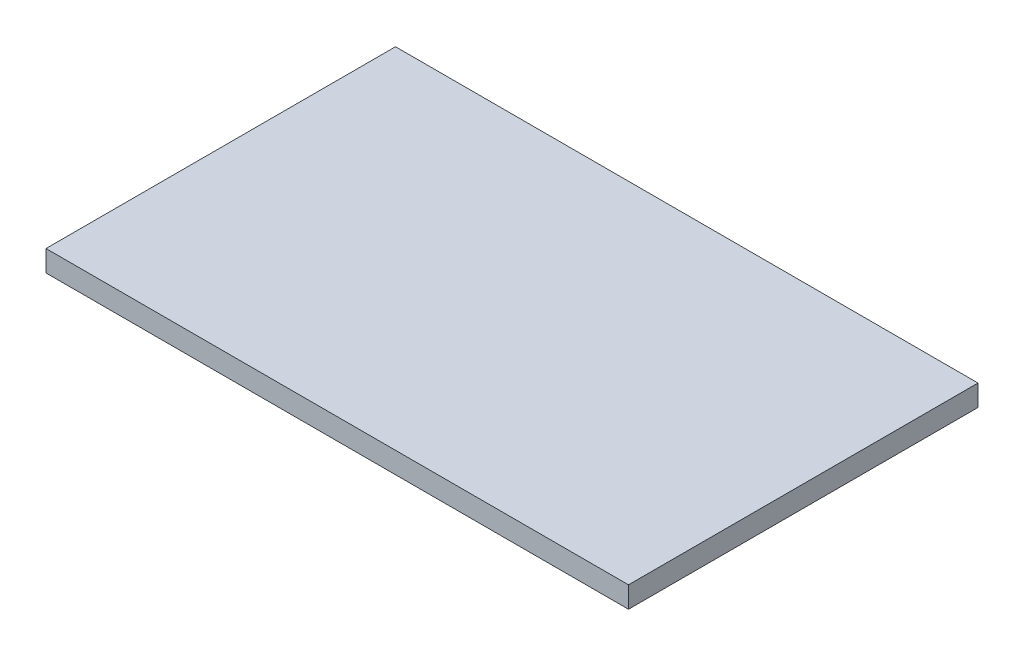
SolidWorks part; units mm, degrees
material "ABS"
ref_plane "Спереди" through (0, 0, 0) normal (0, 0, 1) x (1, 0, 0)
ref_plane "Сверху" through (0, 0, 0) normal (0, 1, 0) x (1, 0, 0)
ref_plane "Справа" through (0, 0, 0) normal (1, 0, 0) x (0, 0, -1)
sketch "Эскиз1" plane through (0, 0, 0) normal (0, 1, 0) x (1, 0, 0)
  line L1 (0, 0) -> (550, 0)
  line L2 (0, 0) -> (0, 330)
  line L3 (0, 330) -> (550, 330)
  line L4 (550, 0) -> (550, 330)
  dimension "D1" = 330
  dimension "D2" = 550
extrude "Бобышка-Вытянуть1" add sketch "Эскиз1" along normal blind 20
sketch "Эскиз2" plane through (0, 0, 0) normal (0, -1, 0) x (1, 0, 0)
  line L0 (550, -330) -> (0, -330) construction
  line L1 (10, -10) -> (540, -10)
  line L2 (10, -10) -> (10, -320)
  line L3 (10, -320) -> (540, -320)
  line L4 (540, -10) -> (540, -320)
  line L6 (0, 0) -> (550, 0) construction
  line L7 (550, 0) -> (550, -330) construction
  dimension "D1" = 10
  dimension "D2" = 10
  dimension "D3" = 10
  dimension "D4" = 10
extrude "Вырез-Вытянуть1" cut sketch "Эскиз2" against normal blind 3
